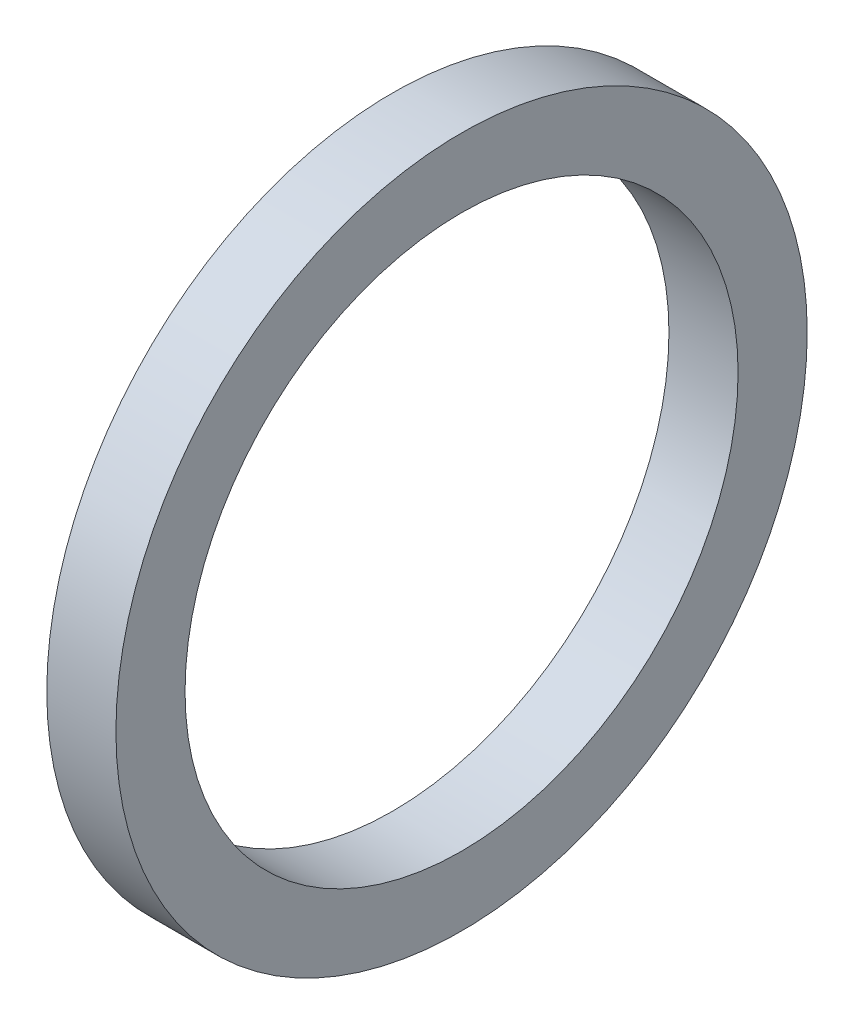
SolidWorks part; units mm, degrees
ref_plane "Alzado" through (0, 0, 0) normal (0, 0, 1) x (1, 0, 0)
ref_plane "Planta" through (0, 0, 0) normal (0, 1, 0) x (1, 0, 0)
ref_plane "Vista lateral" through (0, 0, 0) normal (1, 0, 0) x (0, 0, -1)
ref_plane "Plane1" through (0, 0, 0) normal (0, 0, 1) x (1, 0, 0)
sketch "Sketch1" plane through (0, 0, 0) normal (0, 0, 1) x (1, 0, 0)
  line L0 (0, 8) -> (2, 8)
  line L1 (2, 8) -> (2, 10)
  line L2 (2, 10) -> (0, 10)
  line L3 (0, 10) -> (0, 8)
  line L4 (2, 0) -> (0, 0) construction
revolve "Revolve1" add sketch "Sketch1" angle 360 about L4
